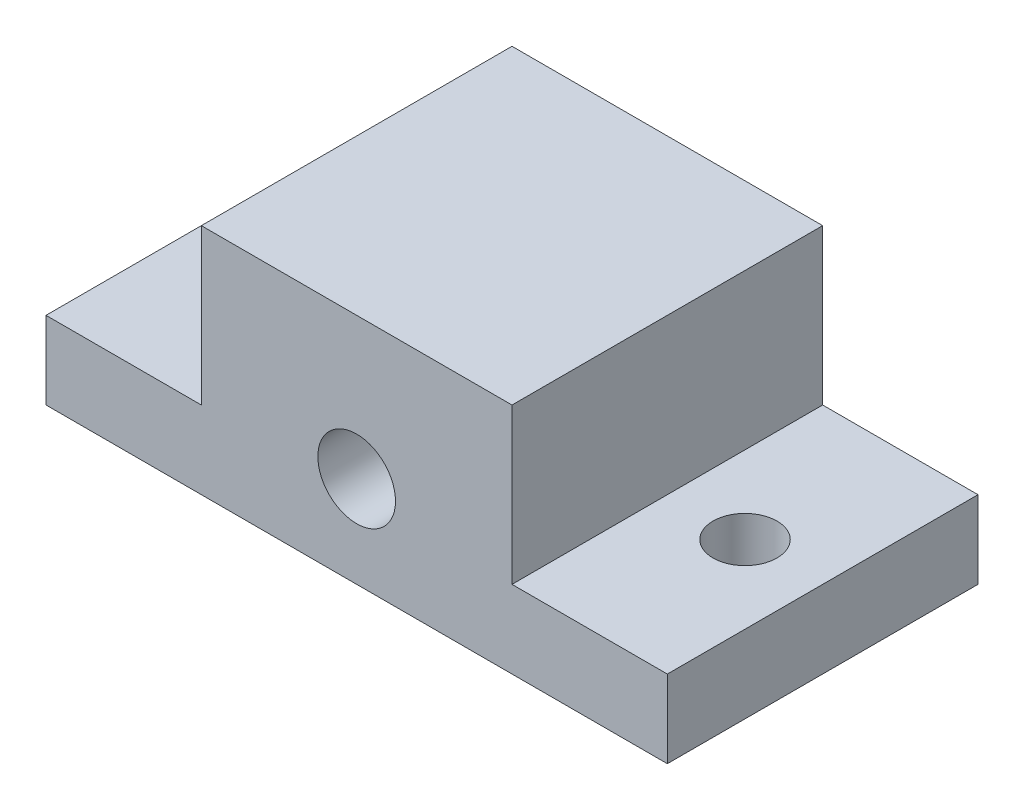
SolidWorks part; units mm, degrees
ref_plane "Front Plane" through (0, 0, 0) normal (0, 0, 1) x (1, 0, 0)
ref_plane "Top Plane" through (0, 0, 0) normal (0, 1, 0) x (1, 0, 0)
ref_plane "Right Plane" through (0, 0, 0) normal (1, 0, 0) x (0, 0, -1)
sketch "Sketch1" plane through (0, 0, 0) normal (0, 0, 1) x (1, 0, 0)
  line L1 (-12.7, 4.7625) -> (12.7, 4.7625)
  line L2 (-12.7, 4.7625) -> (-12.7, -4.7625)
  line L3 (-12.7, -4.7625) -> (12.7, -4.7625)
  line L4 (12.7, 4.7625) -> (12.7, -4.7625)
  line L5 (-12.7, 4.7625) -> (12.7, -4.7625) construction
  line L6 (-12.7, -4.7625) -> (12.7, 4.7625) construction
  point P0 (0, 0)
  dimension "D1" = 9.525
  dimension "D2" = 25.4
extrude "Boss-Extrude1" add sketch "Sketch1" along normal blind 12.7
sketch "Sketch2" plane through (0, 0, 12.7) normal (0, 0, 1) x (1, 0, 0)
  line L0 (-12.7, -4.7625) -> (12.7, -4.7625) construction
  line L2 (-12.7, 4.7625) -> (-6.35, 4.7625)
  line L3 (-12.7, 4.7625) -> (-12.7, -1.5875)
  line L4 (-12.7, -1.5875) -> (-6.35, -1.5875)
  line L5 (-6.35, 4.7625) -> (-6.35, -1.5875)
  line L6 (12.7, 4.7625) -> (6.35, 4.7625)
  line L7 (12.7, 4.7625) -> (12.7, -1.5875)
  line L8 (12.7, -1.5875) -> (6.35, -1.5875)
  line L9 (6.35, 4.7625) -> (6.35, -1.5875)
  circle A0 centre (0, -1.0287) radius 1.5875
  dimension "D1" = 3.7338
  dimension "D2" = 3.175
  dimension "D3" = 3.175
  dimension "D4" = 6.35
extrude "Cut-Extrude1" cut sketch "Sketch2" against normal through all
sketch "Sketch4" plane through (0, -1.5875, 0) normal (0, 1, 0) x (1, 0, 0)
  line L0 (12.7, 0) -> (12.7, -12.7) construction
  line L1 (-12.7, 0) -> (-12.7, -12.7) construction
  circle A0 centre (9.525, -6.35) radius 1.3088
  circle A1 centre (-9.525, -6.35) radius 1.3088
  dimension "D1" = 3.175
  dimension "D2" = 3.175
extrude "Cut-Extrude2" cut sketch "Sketch4" against normal through all
